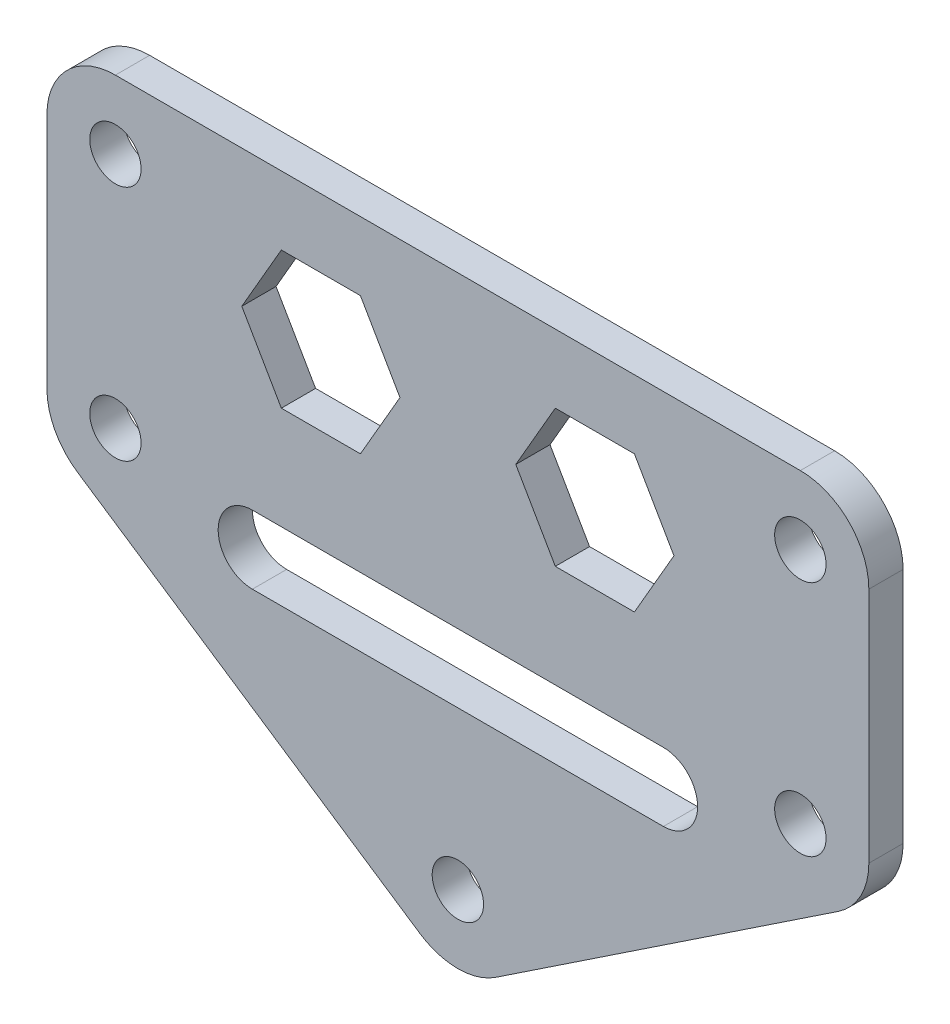
SolidWorks part; units mm, degrees
ref_plane "Front Plane" through (0, 0, 0) normal (0, 0, 1) x (1, 0, 0)
ref_plane "Top Plane" through (0, 0, 0) normal (0, 1, 0) x (1, 0, 0)
ref_plane "Right Plane" through (0, 0, 0) normal (1, 0, 0) x (0, 0, -1)
sketch "Sketch1" plane through (0, 0, 0) normal (0, 0, 1) x (1, 0, 0)
  line L0 (7.0447, 4.6965) -> (70.5447, 47.0298)
  line L1 (76.2, 57.5968) -> (76.2, 101.6)
  line L2 (63.5, 114.3) -> (-63.5, 114.3)
  line L3 (-76.2, 101.6) -> (-76.2, 57.5968)
  line L4 (-70.5447, 47.0298) -> (-7.0447, 4.6965)
  line L5 (0, -55) -> (0, 55) construction
  line L6 (55, 0) -> (-55, 0) construction
  line L7 (-38.1, 57.15) -> (38.1, 57.15)
  line L8 (-38.1, 44.45) -> (38.1, 44.45)
  line L10 (-10.7353, 88.9) -> (-18.0677, 101.6)
  line L11 (-18.0677, 101.6) -> (-32.7323, 101.6)
  line L12 (-32.7323, 101.6) -> (-40.0647, 88.9)
  line L13 (-40.0647, 88.9) -> (-32.7323, 76.2)
  line L14 (-32.7323, 76.2) -> (-18.0677, 76.2)
  line L15 (-18.0677, 76.2) -> (-10.7353, 88.9)
  line L16 (40.0647, 88.9) -> (32.7323, 101.6)
  line L17 (32.7323, 101.6) -> (18.0677, 101.6)
  line L18 (18.0677, 101.6) -> (10.7353, 88.9)
  line L19 (10.7353, 88.9) -> (18.0677, 76.2)
  line L20 (18.0677, 76.2) -> (32.7323, 76.2)
  line L21 (32.7323, 76.2) -> (40.0647, 88.9)
  arc A0 (70.5447, 47.0298) -> (76.2, 57.5968) centre (63.5, 57.5968) ccw
  arc A1 (7.0447, 4.6965) -> (-7.0447, 4.6965) centre (0, 15.2635) cw
  arc A2 (-76.2, 57.5968) -> (-70.5447, 47.0298) centre (-63.5, 57.5968) ccw
  arc A3 (-63.5, 114.3) -> (-76.2, 101.6) centre (-63.5, 101.6) ccw
  arc A4 (76.2, 101.6) -> (63.5, 114.3) centre (63.5, 101.6) ccw
  circle A5 centre (-63.5, 101.6) radius 4.7625
  circle A6 centre (-63.5, 57.5968) radius 4.7625
  circle A7 centre (63.5, 101.6) radius 4.7625
  circle A8 centre (63.5, 57.5968) radius 4.7625
  arc A9 (38.1, 44.45) -> (38.1, 57.15) centre (38.1, 50.8) ccw
  arc A10 (-38.1, 57.15) -> (-38.1, 44.45) centre (-38.1, 50.8) ccw
  circle A11 centre (0, 15.2635) radius 4.7625
  circle A12 centre (-25.4, 88.9) radius 12.7 construction
  circle A13 centre (25.4, 88.9) radius 12.7 construction
  point P12 (76.2, 50.8)
  point P15 (0, 0)
  point P18 (-76.2, 50.8)
  point P21 (-76.2, 114.3)
  point P24 (76.2, 114.3)
  dimension "D5" = 12.7
  dimension "D7" = 9.525
  dimension "D12" = 12.7
  dimension "D13" = 25.4
  dimension "D1" = 152.4
  dimension "D2" = 76.2
  dimension "D3" = 63.5
  dimension "D4" = 50.8
  dimension "D6" = 50.8
  dimension "D8" = 0
  dimension "D9" = 50.8
  dimension "D10" = 76.2
  dimension "D11" = 38.1
  dimension "D14" = 50.8
  dimension "D15" = 25.4
  dimension "D16" = 25.4
  dimension "D17" = 12.7
  dimension "D18" = 25.4
extrude "Boss-Extrude1" add sketch "Sketch1" along normal blind 6.35
